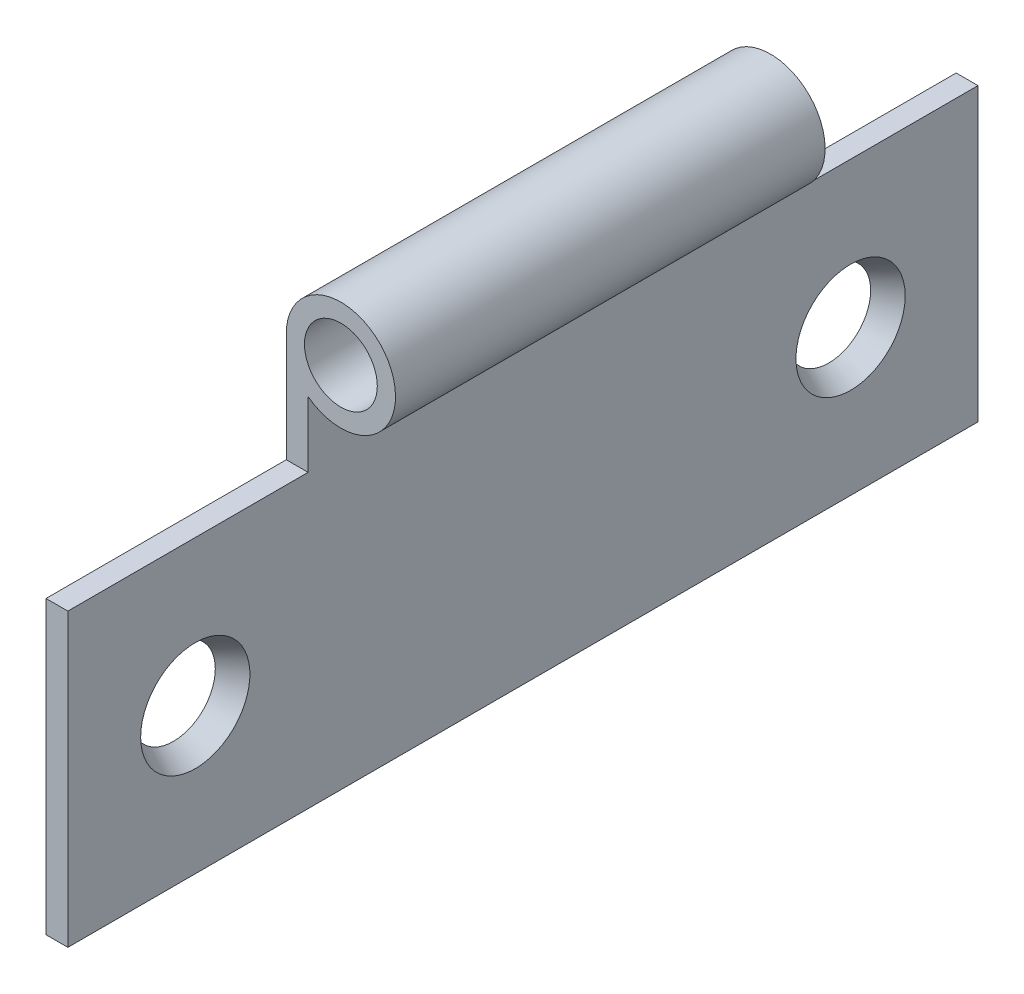
SolidWorks part; units mm, degrees
ref_plane "前视基准面" through (0, 0, 0) normal (0, 0, 1) x (1, 0, 0)
ref_plane "上视基准面" through (0, 0, 0) normal (0, 1, 0) x (1, 0, 0)
ref_plane "右视基准面" through (0, 0, 0) normal (1, 0, 0) x (0, 0, -1)
sketch "草图1" plane through (0, 0, 0) normal (0, 0, 1) x (1, 0, 0)
  line L0 (0, 0) -> (0, 11)
  dimension "D1" = 11
extrude "拉伸-薄壁1" add sketch "草图1" along normal mid plane 25 thin
sketch "草图2" plane through (0, 0, 12.5) normal (0, 0, 1) x (1, 0, 0)
  line L0 (0, 0) -> (0, 11) construction
  line L1 (0, 11) -> (3.5271, 11) construction
  circle A0 centre (1.5, 11) radius 1.5
  dimension "D1" = 3
sweep "扫描1" add profiles "草图2" path edge at (0.6, 11, 0)
sketch "草图3" plane through (0, 0, 12.5) normal (0, 0, 1) x (1, 0, 0)
  circle A0 centre (1.5, 11) radius 1
  dimension "D1" = 2
extrude "切除-拉伸1" cut sketch "草图3" against normal through all
sketch "草图10" plane through (0.6, 0, 0) normal (1, 0, 0) x (0, 0, -1)
  line L0 (-5.9, 14) -> (-13.7704, 14)
  line L1 (-13.7704, 14) -> (-13.7704, 8)
  line L2 (0, -0.5102) -> (0, 25.1077) construction
  line L4 (-13.7704, 8) -> (-5.9, 8)
  line L5 (13.7704, 8) -> (5.9, 8)
  line L6 (13.7704, 14) -> (13.7704, 8)
  line L7 (5.9, 14) -> (13.7704, 14)
  line L8 (-12.5, 0) -> (12.5, 0) construction
  line L10 (-5.9, 14) -> (-5.9, 8)
  line L11 (5.9, 14) -> (5.9, 8)
  dimension "D3" = 11.8
  dimension "D5" = 6
  dimension "D1" = 8
extrude "切除-拉伸4" cut sketch "草图10" against normal mid plane 120
sketch "草图11" plane through (0.6, 0, 0) normal (1, 0, 0) x (0, 0, -1)
  line L0 (0, -4.9447) -> (0, 29.1666) construction
  line L1 (17.138, 4) -> (-14.121, 4) construction
  circle A0 centre (9, 4) radius 1.5
  dimension "D1" = 3
  dimension "D2" = 9
sketch "草图12" plane through (0, 0, 0) normal (-1, 0, 0) x (0, 0, 1)
  circle A0 centre (-9, 4) radius 1.15
  dimension "D1" = 2.3
loft "切除-放样1" cut profiles "草图12", "草图11"
mirror "镜向1" about plane through (0, 0, 0) normal (0, 0, 1) of "切除-放样1"
